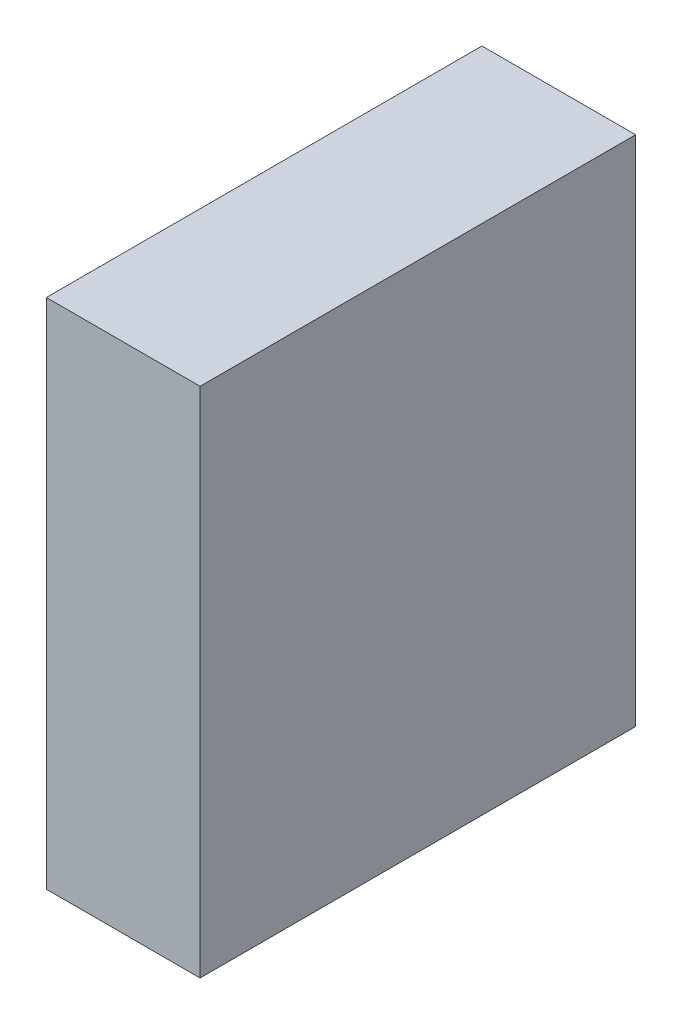
SolidWorks part; units mm, degrees
ref_plane "Front Plane" through (0, 0, 0) normal (0, 0, 1) x (1, 0, 0)
ref_plane "Top Plane" through (0, 0, 0) normal (0, 1, 0) x (1, 0, 0)
ref_plane "Right Plane" through (0, 0, 0) normal (1, 0, 0) x (0, 0, -1)
sketch "Sketch1" plane through (0, 0, 0) normal (0, 1, 0) x (1, 0, 0)
  line L1 (-38.1, -107.95) -> (38.1, -107.95)
  line L2 (-38.1, -107.95) -> (-38.1, 107.95)
  line L3 (-38.1, 107.95) -> (38.1, 107.95)
  line L4 (38.1, -107.95) -> (38.1, 107.95)
  line L5 (-38.1, -107.95) -> (38.1, 107.95) construction
  line L6 (-38.1, 107.95) -> (38.1, -107.95) construction
  point P0 (0, 0)
  dimension "D1" = 215.9
  dimension "D2" = 76.2
extrude "Boss-Extrude1" add sketch "Sketch1" along normal blind 254
sketch "Sketch2" plane through (0, 254, 0) normal (0, 1, 0) x (1, 0, 0)
  line L0 (38.1, -107.95) -> (38.1, 107.95) construction
  line L1 (-38.1, 107.95) -> (38.1, 107.95)
  line L2 (-38.1, 107.95) -> (-38.1, 0)
  line L3 (-38.1, 0) -> (38.1, 0)
  line L4 (38.1, 107.95) -> (38.1, 0)
sketch "Sketch3" plane through (0, 254, 0) normal (0, 1, 0) x (1, 0, 0)
  line L1 (38.1, -107.95) -> (-38.1, -107.95)
  line L2 (38.1, -107.95) -> (38.1, 0)
  line L3 (38.1, 0) -> (-38.1, 0)
  line L4 (-38.1, -107.95) -> (-38.1, 0)
